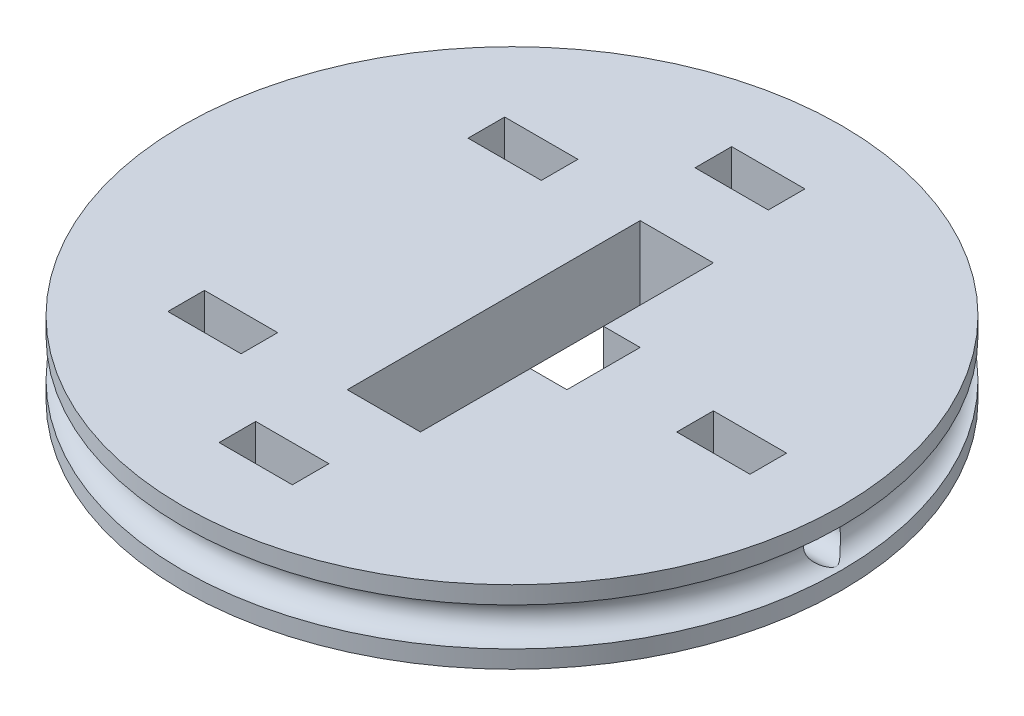
SolidWorks part; units mm, degrees
ref_plane "Alzado" through (0, 0, 0) normal (0, 0, 1) x (1, 0, 0)
ref_plane "Planta" through (0, 0, 0) normal (0, 1, 0) x (1, 0, 0)
ref_plane "Vista lateral" through (0, 0, 0) normal (1, 0, 0) x (0, 0, -1)
sketch "Croquis1" plane through (0, 0, 0) normal (1, 0, 0) x (0, 0, -1)
  line L0 (0, 59.0708) -> (0, -40.8641) construction
  line L1 (-45, 2.6) -> (-45, 5)
  line L2 (0, 5) -> (0, -5)
  line L3 (-45, -5) -> (-45, -2.6)
  line L8 (-45, 5) -> (0, 5)
  line L10 (0, -5) -> (-45, -5)
  arc A1 (-45, -2.6) -> (-45, 2.6) centre (-45, 0) ccw
  point P3 (-50, 0)
  dimension "D2" = 5
  dimension "D1" = 2.6
  dimension "D3" = 45
revolve "Revolución1" add sketch "Croquis1" angle 360 about L0
sketch "Croquis2" plane through (0, 5, 0) normal (0, 1, 0) x (1, 0, 0)
  line L0 (7.5, 5) -> (7.5, 20)
  line L1 (-2.5, -20) -> (7.5, -20)
  line L2 (-2.5, -20) -> (-2.5, 20)
  line L3 (-2.5, 20) -> (7.5, 20)
  line L4 (7.5, -20) -> (7.5, -5)
  line L5 (12.5, -5) -> (7.5, -5)
  line L6 (12.5, -5) -> (12.5, 5)
  line L7 (12.5, 5) -> (7.5, 5)
  line L8 (0, 0) -> (0, 49.6044) construction
  line L9 (12.5, -5) -> (7.5, 5) construction
  line L10 (12.5, 5) -> (7.5, -5) construction
  line L11 (5, 30) -> (-5, 30)
  line L12 (5, 30) -> (5, 35)
  line L13 (5, 35) -> (-5, 35)
  line L14 (-5, 30) -> (-5, 35)
  line L15 (5, 30) -> (-5, 35) construction
  line L16 (5, 35) -> (-5, 30) construction
  line L17 (-34.098, 0) -> (51.4641, 0) construction
  line L18 (5, -30) -> (5, -35)
  line L19 (5, -30) -> (-5, -30)
  line L20 (-5, -30) -> (-5, -35)
  line L21 (5, -35) -> (-5, -35)
  line L23 (25, -2.5) -> (35, -2.5)
  line L24 (25, -2.5) -> (25, 2.5)
  line L25 (25, 2.5) -> (35, 2.5)
  line L26 (35, -2.5) -> (35, 2.5)
  line L27 (25, -2.5) -> (35, 2.5) construction
  line L28 (25, 2.5) -> (35, -2.5) construction
  point P5 (30, 0)
  point P6 (10, 0)
  dimension "D1" = 30
  dimension "D2" = 40
  dimension "D3" = 5
  dimension "D4" = 10
  dimension "D5" = 5
  dimension "D6" = 10
  dimension "D7" = 35
  dimension "D8" = 10
  dimension "D9" = 5
extrude "Cortar-Extruir1" cut sketch "Croquis2" against normal blind 10
sketch "Croquis3" plane through (12.5, 0, 0) normal (-1, 0, 0) x (0, 0, 1)
  circle A0 centre (0, 0) radius 2.5
  dimension "D1" = 5
extrude "Cortar-Extruir2" cut sketch "Croquis3" against normal blind 50
sketch "Croquis4" plane through (0, 5, 0) normal (0, 1, 0) x (1, 0, 0)
  line L4 (7.5, 12.5) -> (25, 2.5)
  line L5 (25, 2.5) -> (25, -2.5)
  line L6 (25, 2.5) -> (25, -2.5)
  line L7 (7.5, 5) -> (12.5, 5)
  line L8 (12.5, 5) -> (12.5, -5)
  line L9 (12.5, -5) -> (7.5, -5)
  line L10 (7.5, -5) -> (12.5, -5) construction
  line L11 (7.5, 5) -> (7.5, 20) construction
  line L12 (25, -2.5) -> (7.5, -12.5)
  line L13 (7.5, -20) -> (7.5, -5) construction
  line L14 (7.5, -12.5) -> (7.5, -5)
  line L15 (7.5, 5) -> (7.5, 12.5)
  circle A0 centre (0, 0) radius 30 construction
  dimension "D1" = 60
  dimension "D2" = 0
extrude "Saliente-Extruir1" add sketch "Croquis4" against normal blind 15
sketch "Croquis5" plane through (0, 5, 0) normal (0, 1, 0) x (1, 0, 0)
  line L0 (0, 0) -> (-58.2892, 0) construction
  line L1 (-24, -18) -> (-24, -23)
  line L2 (-14, 18) -> (-24, 18)
  line L3 (-14, 18) -> (-14, 23)
  line L4 (-14, 23) -> (-24, 23)
  line L5 (-24, 18) -> (-24, 23)
  line L6 (-14, -23) -> (-24, -23)
  line L7 (-14, -18) -> (-14, -23)
  line L8 (-14, -18) -> (-24, -18)
  dimension "D1" = 5
  dimension "D2" = 10
  dimension "D3" = 18
  dimension "D4" = 14
extrude "Cortar-Extruir3" cut sketch "Croquis5" against normal blind 10
